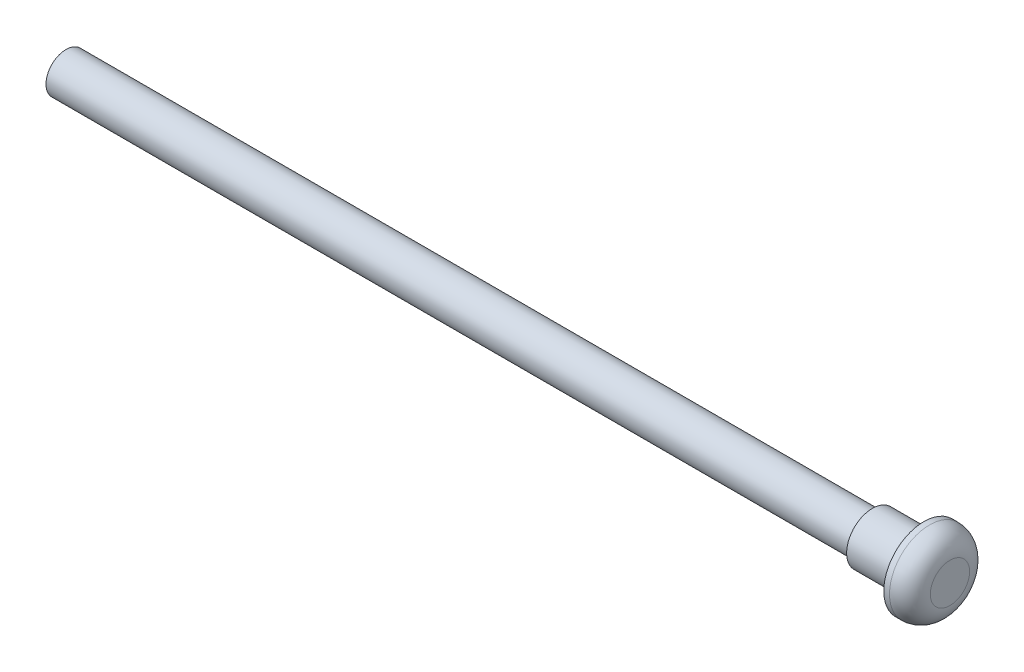
SolidWorks part; units mm, degrees
ref_plane "Front Plane" through (0, 0, 0) normal (0, 0, 1) x (1, 0, 0)
ref_plane "Top Plane" through (0, 0, 0) normal (0, 1, 0) x (1, 0, 0)
ref_plane "Right Plane" through (0, 0, 0) normal (1, 0, 0) x (0, 0, -1)
sketch "Sketch1" plane through (0, 0, 0) normal (0, 0, 1) x (1, 0, 0)
  line L0 (0, 0) -> (152, 0)
  line L1 (0, 0) -> (0, 3.5)
  line L2 (0, 3.5) -> (141, 3.5)
  line L3 (141, 3.5) -> (141, 4.5)
  line L4 (141, 4.5) -> (150, 4.5)
  line L5 (150, 4.5) -> (150, 7)
  line L6 (150, 7) -> (151, 7)
  line L7 (152, 0) -> (152, 22.5957) construction
  line L8 (154.5714, 3.4286) -> (154.5714, 0)
  line L9 (154.5714, 0) -> (152, 0)
  arc A1 (151, 7) -> (154.5714, 3.4286) centre (151, 3.4286) cw
  dimension "D1" = 152
  dimension "D2" = 3.5
  dimension "D3" = 7
  dimension "D4" = 1
  dimension "D5" = 1
  dimension "D6" = 9
  dimension "D7" = 1
revolve "Revolve2" add sketch "Sketch1" angle 360 about L0
